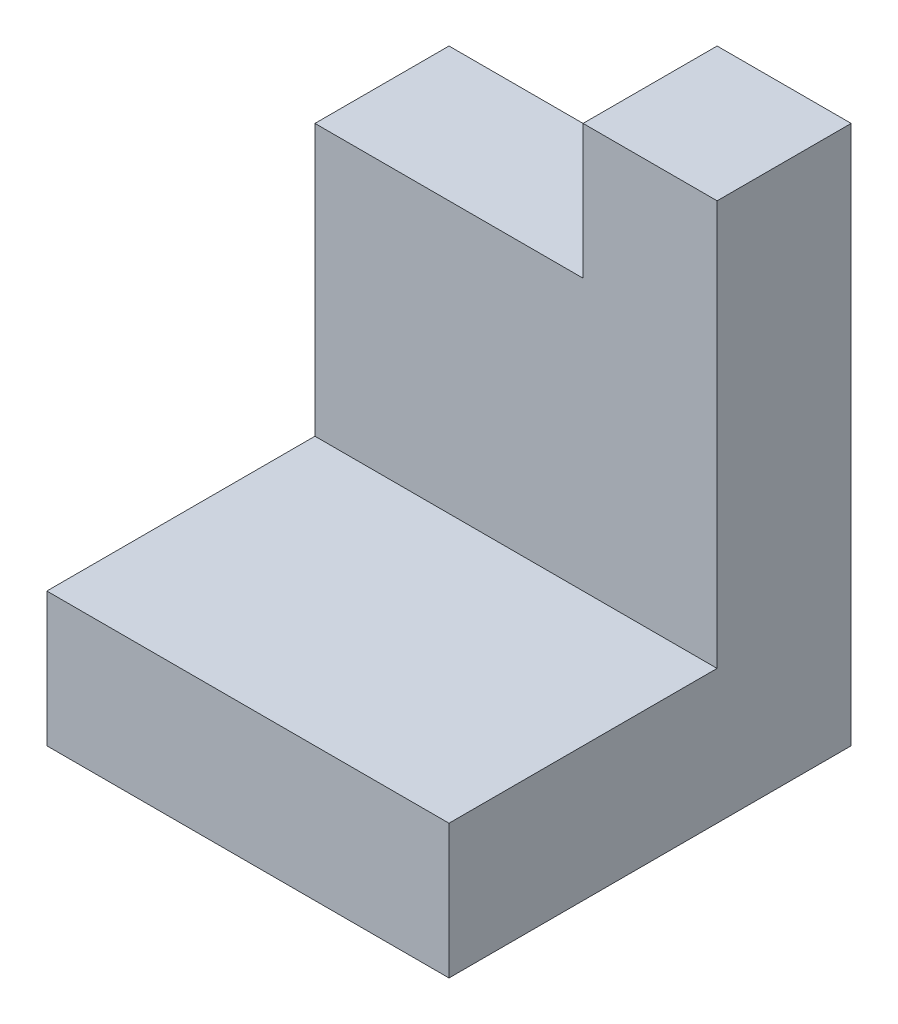
SolidWorks part; units mm, degrees
ref_plane "Plano frontal" through (0, 0, 0) normal (0, 0, 1) x (1, 0, 0)
ref_plane "Plano superior" through (0, 0, 0) normal (0, 1, 0) x (1, 0, 0)
ref_plane "Plano direito" through (0, 0, 0) normal (1, 0, 0) x (0, 0, -1)
sketch "Esboço1" plane through (0, 0, 0) normal (0, 0, 1) x (1, 0, 0)
  line L1 (0, 0) -> (60, 0)
  line L2 (0, 0) -> (0, 20)
  line L3 (0, 20) -> (60, 20)
  line L4 (60, 0) -> (60, 20)
  dimension "D1" = 60
  dimension "D2" = 20
extrude "Ressalto-extrusão1" add sketch "Esboço1" along normal blind 40
sketch "Esboço2" plane through (0, 0, 0) normal (0, 0, -1) x (-1, 0, 0)
  line L1 (-60, 0) -> (0, 0)
  line L2 (-60, 0) -> (-60, 60.4178)
  line L3 (-60, 60.4178) -> (0, 60.4178)
  line L4 (0, 0) -> (0, 60.4178)
extrude "Ressalto-extrusão2" add sketch "Esboço2" along normal blind 20
sketch "Esboço3" plane through (0, 60.4178, 0) normal (0, 1, 0) x (1, 0, 0)
  line L0 (0, 0) -> (60, 0) construction
  line L1 (60, 20) -> (40, 20)
  line L2 (60, 20) -> (60, 0)
  line L3 (60, 0) -> (40, 0)
  line L4 (40, 20) -> (40, 0)
  dimension "D1" = 20
extrude "Ressalto-extrusão3" add sketch "Esboço3" along normal blind 20
